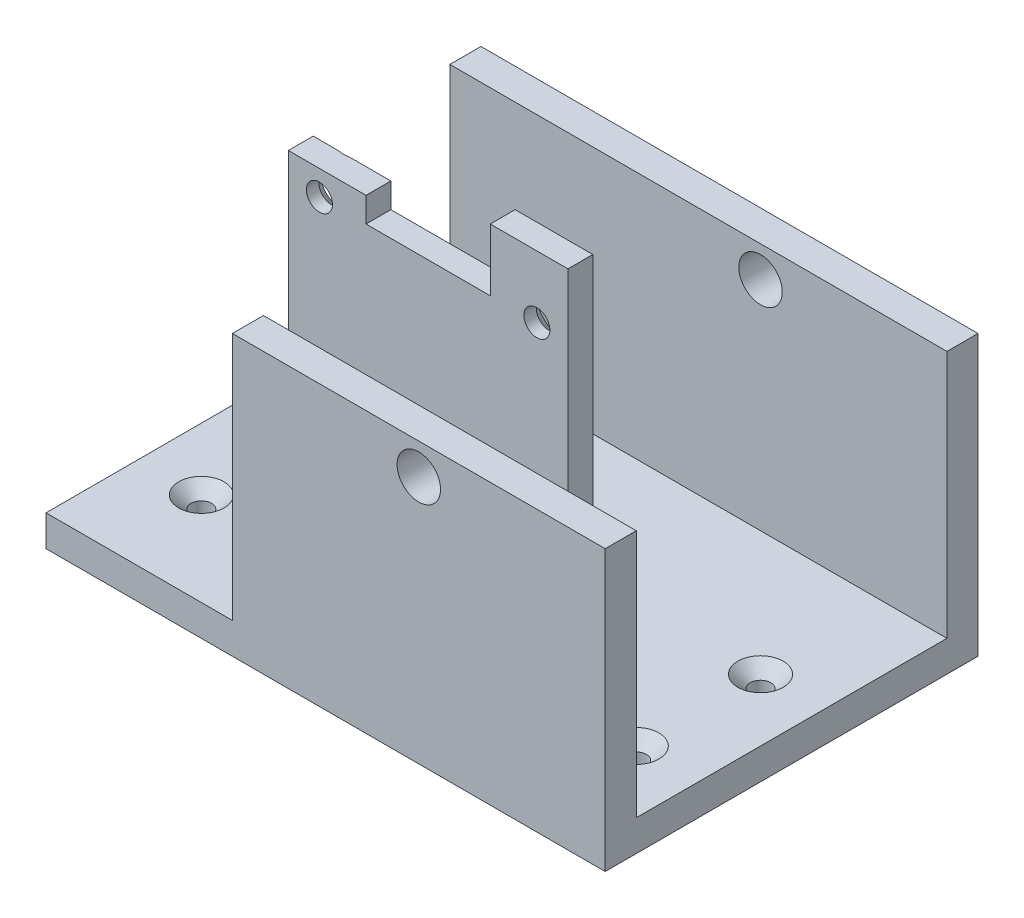
SolidWorks part; units mm, degrees
ref_plane "Ebene vorne" through (0, 0, 0) normal (0, 0, 1) x (1, 0, 0)
ref_plane "Ebene oben" through (0, 0, 0) normal (0, 1, 0) x (1, 0, 0)
ref_plane "Ebene rechts" through (0, 0, 0) normal (1, 0, 0) x (0, 0, -1)
sketch "Skizze1" plane through (0, 0, 0) normal (0, 1, 0) x (1, 0, 0)
  line L1 (-45, -30) -> (45, -30)
  line L2 (-45, -30) -> (-45, 30)
  line L3 (-45, 30) -> (45, 30)
  line L4 (45, -30) -> (45, 30)
  line L5 (-45, -30) -> (45, 30) construction
  line L6 (-45, 30) -> (45, -30) construction
  point P0 (0, 0)
  dimension "D1" = 90
  dimension "D2" = 60
extrude "Aufsatz-Linear austragen1" add sketch "Skizze1" along normal blind 5 contours L2 L1 L4 L3
sketch "Skizze2" plane through (0, 5, 0) normal (0, 1, 0) x (1, 0, 0)
  line L0 (45, -30) -> (45, 30) construction
  line L1 (-45, 30) -> (45, 30)
  line L2 (-45, 30) -> (-45, 25)
  line L3 (-45, 25) -> (45, 25)
  line L4 (45, 30) -> (45, 25)
  line L12 (-45, -30) -> (45, -30)
  line L13 (-45, -30) -> (-45, -25)
  line L14 (-45, -25) -> (45, -25)
  line L15 (45, -30) -> (45, -25)
  dimension "D1" = 5
  dimension "D2" = 5
extrude "Aufsatz-Linear austragen2" add sketch "Skizze2" along normal blind 40
sketch "Skizze3" plane through (0, 5, 0) normal (0, 1, 0) x (1, 0, 0)
  line L1 (-45, 13.0042) -> (0, 13.0042)
  line L2 (-45, 13.0042) -> (-45, 9.0042)
  line L3 (-45, 9.0042) -> (0, 9.0042)
  line L4 (0, 13.0042) -> (0, 9.0042)
  line L9 (-36.5, 9.0042) -> (-8.5, 9.0042) construction
  line L10 (-36.5, 9.0042) -> (-36.5, -9.9958) construction
  line L11 (-36.5, -9.9958) -> (-8.5, -9.9958) construction
  line L12 (-8.5, 9.0042) -> (-8.5, -9.9958) construction
  line L13 (-30, 19.7959) -> (-15, 19.7959) construction
  line L19 (-30, 19.7959) -> (-30, 14.0042) construction
  line L24 (-30, 14.0042) -> (-15, 14.0042) construction
  line L25 (-15, 19.7959) -> (-15, 14.0042) construction
  line L26 (-15, 14.0042) -> (45, 14.0042) construction
  line L27 (-15, 14.0042) -> (-15, 19.7959) construction
  line L28 (-15, 19.7959) -> (45, 19.7959) construction
  line L29 (45, 14.0042) -> (45, 19.7959) construction
  dimension "D1" = 45
  dimension "D2" = 19
  dimension "D3" = 28
  dimension "D4" = 8.5
  dimension "D5" = 4
  dimension "D6" = 15
  dimension "D7" = 60
extrude "Aufsatz-Linear austragen3" add sketch "Skizze3" along normal blind 37 contours L2 L1 L4 L3
sketch "Skizze4" plane through (0, 0, -9.0042) normal (0, 0, 1) x (1, 0, 0)
  line L0 (-45, 42) -> (0, 42) construction
  line L5 (-32.5, 42) -> (-12.5, 42)
  line L6 (-32.5, 42) -> (-32.5, 32)
  line L7 (-32.5, 32) -> (-12.5, 32)
  line L8 (-12.5, 42) -> (-12.5, 32)
  line L10 (0, 42) -> (0, 5) construction
  line L11 (-45, 42) -> (-45, 5) construction
  circle A0 centre (-40, 32) radius 2.1
  circle A1 centre (-5, 32) radius 2.1
  dimension "D8" = 4.2
  dimension "D9" = 4.2
  dimension "D1" = 20
  dimension "D2" = 10
  dimension "D3" = 12.5
  dimension "D4" = 5
  dimension "D5" = 10
  dimension "D6" = 10
  dimension "D7" = 5
extrude "Schnitt-Linear austragen1" cut sketch "Skizze4" against normal blind 5
chamfer "Fase1" distance 2 angle 45 1 edges at (-42.1, 32, -13.0042)
chamfer "Fase2" distance 2 angle 45 1 edges at (-7.1, 32, -13.0042)
sketch "Skizze6" plane through (0, 0, -30) normal (0, 0, -1) x (-1, 0, 0)
  line L0 (-45, 45) -> (-45, 0) construction
  line L1 (45, 0) -> (-45, 0) construction
  circle A0 centre (-15, 40) radius 3.5
  circle A1 centre (-15, 40) radius 30 construction
  circle A2 centre (22.5, 40) radius 7.5 construction
  dimension "D3" = 60
  dimension "D4" = 15
  dimension "D6" = 7
  dimension "D1" = 30
  dimension "D2" = 40
  dimension "D5" = 37.5
extrude "Schnitt-Linear austragen2" cut sketch "Skizze6" against normal blind 5
sketch "Skizze8" plane through (0, 0, 30) normal (0, 0, 1) x (1, 0, 0)
  line L0 (45, 45) -> (45, 0) construction
  line L2 (-45, 0) -> (45, 0) construction
  circle A0 centre (15, 40) radius 3.5
  dimension "D3" = 7
  dimension "D1" = 30
  dimension "D2" = 40
extrude "Schnitt-Linear austragen3" cut sketch "Skizze8" against normal blind 5
sketch "Skizze9" plane through (0, 5, 0) normal (0, 1, 0) x (1, 0, 0)
  line L0 (-45, -25) -> (-45, 9.0042) construction
  line L1 (45, -25) -> (45, 25) construction
  line L2 (45, -25) -> (-45, -25) construction
  line L3 (45, -25) -> (-45, -25) construction
  line L4 (-45, 25) -> (45, 25) construction
  circle A0 centre (35, 5) radius 1.65
  circle A1 centre (35, -15) radius 1.65
  circle A2 centre (-35, -15) radius 1.65
  circle A3 centre (-35, 5) radius 1.65
  dimension "D1" = 3.3
  dimension "D8" = 3.3
  dimension "D2" = 10
  dimension "D3" = 10
  dimension "D4" = 10
  dimension "D5" = 10
  dimension "D6" = 10
  dimension "D7" = 20
extrude "Schnitt-Linear austragen4" cut sketch "Skizze9" against normal blind 5
chamfer "Fase3" distance 2 angle 45 4 edges at (-35, 5, 16.65) (35, 5, 16.65) (35, 5, -3.35) (-35, 5, -3.35)
sketch "Skizze10" plane through (0, 0, 30) normal (0, 0, 1) x (1, 0, 0)
  line L0 (-45, 0) -> (45, 0) construction
  line L1 (-45, 45) -> (-15, 45)
  line L2 (-45, 45) -> (-45, 5)
  line L3 (-45, 5) -> (-15, 5)
  line L4 (-15, 45) -> (-15, 5)
  dimension "D1" = 5
  dimension "D2" = 30
extrude "Schnitt-Linear austragen5" cut sketch "Skizze10" against normal blind 10
sketch "Skizze11" plane through (0, 0, -9.0042) normal (0, 0, 1) x (1, 0, 0)
  line L0 (-32.5, 42) -> (-32.5, 32) construction
  line L1 (-45, 42) -> (-32.5, 42)
  line L2 (-45, 42) -> (-45, 36.0038)
  line L3 (-45, 36.0038) -> (-32.5, 36.0038)
  line L4 (-32.5, 42) -> (-32.5, 36.0038)
extrude "Schnitt-Linear austragen6" cut sketch "Skizze11" against normal blind 10
sketch "Skizze12" plane through (0, 0, -30) normal (0, 0, -1) x (-1, 0, 0)
  line L0 (45, 0) -> (-45, 0) construction
  line L1 (45, 45) -> (35, 45)
  line L2 (45, 45) -> (45, 5)
  line L3 (45, 5) -> (35, 5)
  line L4 (35, 45) -> (35, 5)
  dimension "D1" = 5
  dimension "D2" = 10
extrude "Schnitt-Linear austragen7" cut sketch "Skizze12" against normal blind 10
